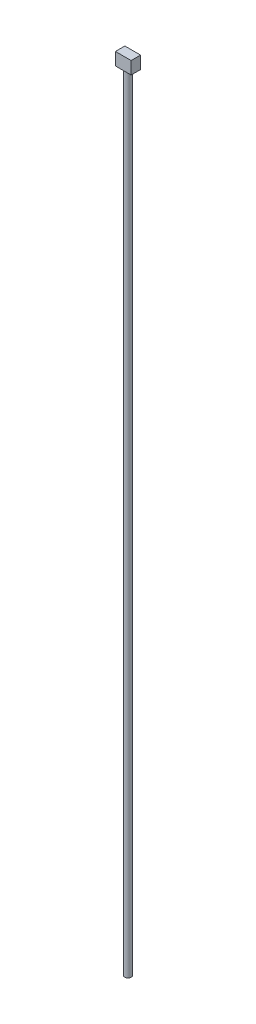
SolidWorks part; units mm, degrees
ref_plane "前视基准面" through (0, 0, 0) normal (0, 0, 1) x (1, 0, 0)
ref_plane "上视基准面" through (0, 0, 0) normal (0, 1, 0) x (1, 0, 0)
ref_plane "右视基准面" through (0, 0, 0) normal (1, 0, 0) x (0, 0, -1)
sketch "草图1" plane through (0, 0, 0) normal (0, 1, 0) x (1, 0, 0)
  circle A0 centre (0, 0) radius 0.525
  dimension "D1" = 1.05
extrude "凸台-拉伸1" add sketch "草图1" along normal blind 125
sketch "草图2" plane through (0, 125, 0) normal (0, 1, 0) x (1, 0, 0)
  line L5 (-1.25, -0.75) -> (1.25, -0.75)
  line L6 (-1.25, -0.75) -> (-1.25, 0.75)
  line L7 (-1.25, 0.75) -> (1.25, 0.75)
  line L8 (1.25, -0.75) -> (1.25, 0.75)
  line L9 (-1.25, -0.75) -> (1.25, 0.75) construction
  line L10 (-1.25, 0.75) -> (1.25, -0.75) construction
  circle A2 centre (0, 0) radius 0.525 construction
  point P0 (-0.525, 0)
  point P1 (0, 0)
  dimension "D1" = 2.5
  dimension "D2" = 1.5
extrude "凸台-拉伸6" add sketch "草图2" along normal blind 2
